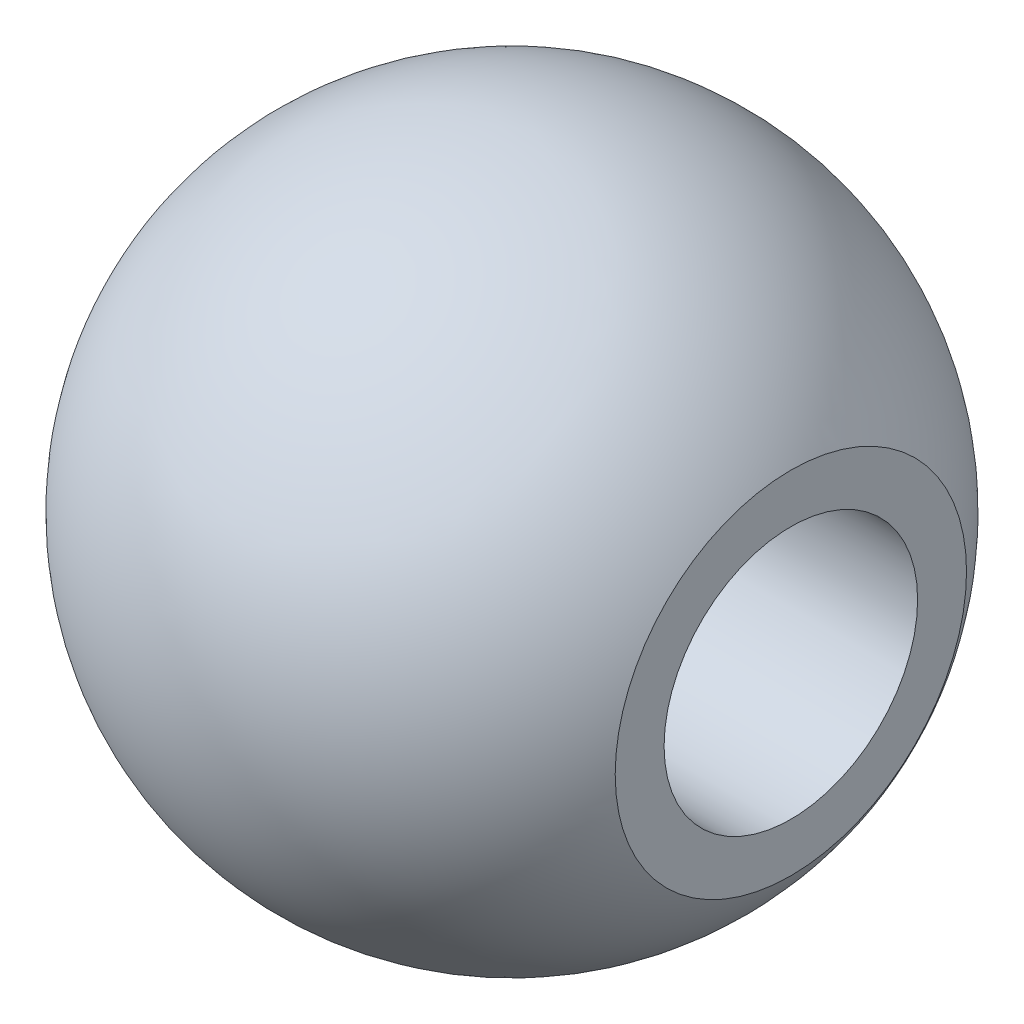
SolidWorks part; units mm, degrees
ref_plane "Front Plane" through (0, 0, 0) normal (0, 0, 1) x (1, 0, 0)
ref_plane "Top Plane" through (0, 0, 0) normal (0, 1, 0) x (1, 0, 0)
ref_plane "Right Plane" through (0, 0, 0) normal (1, 0, 0) x (0, 0, -1)
sketch "Sketch1" plane through (0, 0, 0) normal (0, 0, 1) x (1, 0, 0)
  line L3 (0, 2.6) -> (0, -2.6) construction
  circle A0 centre (0, 0) radius 2.6
  dimension "D1" = 5.2
revolve "Revolve5" add sketch "Sketch1" angle 360 about L3
sketch "Sketch5" plane through (0, 0, 0) normal (0, 0, 1) x (1, 0, 0)
  line L0 (-2.6, 3.9124) -> (-2.6, -4.7689)
  line L1 (-2.6, -4.7689) -> (-2.2, -4.7689)
  line L2 (-2.2, -4.7689) -> (-2.2, 3.9124)
  line L3 (-2.2, 3.9124) -> (-2.6, 3.9124)
  line L4 (2.2, 3.9124) -> (2.6, 3.9124)
  line L5 (2.6, 3.9124) -> (2.6, -4.7689)
  line L6 (2.6, -4.7689) -> (2.2, -4.7689)
  line L7 (2.2, -4.7689) -> (2.2, 3.9124)
  line L8 (2.2, 3.9124) -> (2.6256, 3.9007)
  line L9 (-2.2, 3.9124) -> (2.6256, 3.9007) construction
  line L10 (-2.2, -4.7689) -> (2.2, -4.7689) construction
  circle A0 centre (0, 0) radius 2.6 construction
  dimension "D1" = 4.4
  dimension "D2" = 2.2
extrude "Cut-Extrude3" cut sketch "Sketch5" against normal through all and the other way through all
sketch "Sketch6" plane through (2.2, 0, 0) normal (1, 0, 0) x (0, 0, -1)
  circle A0 centre (0, 0) radius 1
  dimension "D1" = 2
extrude "Cut-Extrude5" cut sketch "Sketch6" against normal through all
